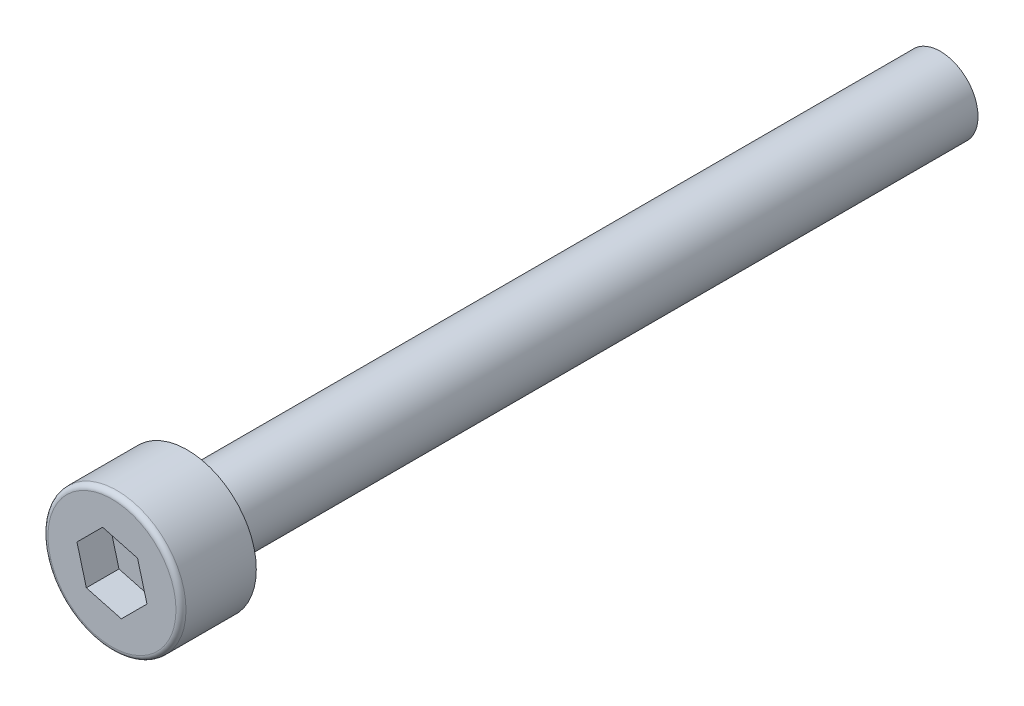
SolidWorks part; units mm, degrees
ref_plane "前视基准面" through (0, 0, 0) normal (0, 0, 1) x (1, 0, 0)
ref_plane "上视基准面" through (0, 0, 0) normal (0, 1, 0) x (1, 0, 0)
ref_plane "右视基准面" through (0, 0, 0) normal (1, 0, 0) x (0, 0, -1)
sketch "草图1" plane through (0, 0, 0) normal (0, 0, 1) x (1, 0, 0)
  circle A0 centre (0, 0) radius 2.75
  dimension "D1" = 5.5
extrude "凸台-拉伸1" add sketch "草图1" along normal blind 3
sketch "草图2" plane through (0, 0, 3) normal (0, 0, 1) x (1, 0, 0)
  line L1 (-1.0206, -1.0206) -> (0.3736, -1.3942)
  line L2 (0.3736, -1.3942) -> (1.3942, -0.3736)
  line L3 (1.3942, -0.3736) -> (1.0206, 1.0206)
  line L4 (1.0206, 1.0206) -> (-0.3736, 1.3942)
  line L5 (-0.3736, 1.3942) -> (-1.3942, 0.3736)
  line L6 (-1.3942, 0.3736) -> (-1.0206, -1.0206)
  circle A0 centre (0, 0) radius 1.25 construction
  dimension "D1" = 2.5
extrude "切除-拉伸1" cut sketch "草图2" against normal blind 1.3
sketch "草图3" plane through (0, 0, 0) normal (0, 0, -1) x (-1, 0, 0)
  circle A0 centre (0, 0) radius 1.5
  dimension "D1" = 3
extrude "凸台-拉伸2" add sketch "草图3" along normal blind 30
fillet "圆角1" radius 0.2
